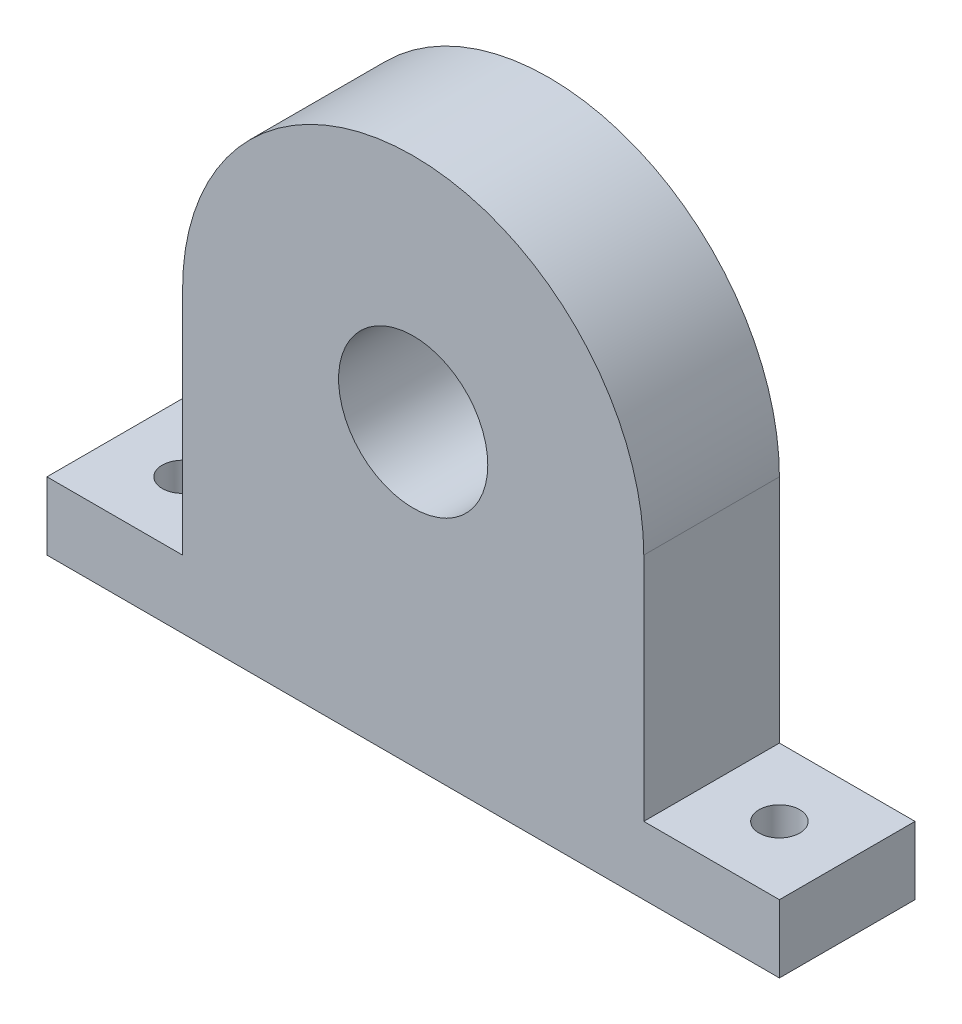
SolidWorks part; units mm, degrees
ref_plane "Спереди" through (0, 0, 0) normal (0, 0, 1) x (1, 0, 0)
ref_plane "Сверху" through (0, 0, 0) normal (0, 1, 0) x (1, 0, 0)
ref_plane "Справа" through (0, 0, 0) normal (1, 0, 0) x (0, 0, -1)
sketch "Эскиз3" plane through (0, 0, 0) normal (0, 0, 1) x (1, 0, 0)
  line L1 (-17, 0) -> (-17, -17)
  line L2 (17, 0) -> (17, -17)
  line L3 (0, -17) -> (0, -22) construction
  line L5 (-27, -17) -> (-27, -22)
  line L6 (27, -17) -> (27, -22)
  line L7 (-17, -17) -> (-27, -17)
  line L8 (-17, -17) -> (-27, -17) construction
  line L9 (27, -17) -> (17, -17)
  line L10 (-17, -17) -> (17, -17) construction
  line L11 (27, -22) -> (-27, -22)
  arc A0 (17, 0) -> (-17, 0) centre (0, 0) ccw
  circle A1 centre (0, 0) radius 5.5
  point P7 (5.0571, -16.2304)
  point P8 (5.0571, -16.2304)
  point P9 (0, -17)
  point P16 (0, -22)
  point P19 (0, -22)
extrude "Бобышка-Вытянуть1" add sketch "Эскиз3" along normal blind 10
sketch "Эскиз4" plane through (0, -17, 0) normal (0, 1, 0) x (1, 0, 0)
  line L0 (27, 0) -> (17, 0) construction
  line L2 (22, 0) -> (22, -5) construction
  line L3 (22, -5) -> (27, -5) construction
  line L5 (27, -10) -> (27, 0) construction
  circle A0 centre (22, -5) radius 1.5
extrude "Вырез-Вытянуть1" cut sketch "Эскиз4" against normal through all
sketch "Эскиз5" plane through (0, -17, 0) normal (0, 1, 0) x (1, 0, 0)
  line L0 (-22, 0) -> (-22, -5) construction
  line L1 (-17, 0) -> (-27, 0) construction
  line L2 (-27, -5) -> (-22, -5) construction
  line L3 (-27, -10) -> (-27, 0) construction
  circle A0 centre (-22, -5) radius 1.5
extrude "Вырез-Вытянуть2" cut sketch "Эскиз5" against normal through all and the other way through all
sketch "Эскиз7" plane through (0, -22, 0) normal (0, -1, 0) x (-1, 0, 0)
  line L0 (22, -5) -> (-22, -5) construction
  line L1 (0, -10) -> (0, 0) construction
  line L2 (27, -10) -> (-27, -10) construction
